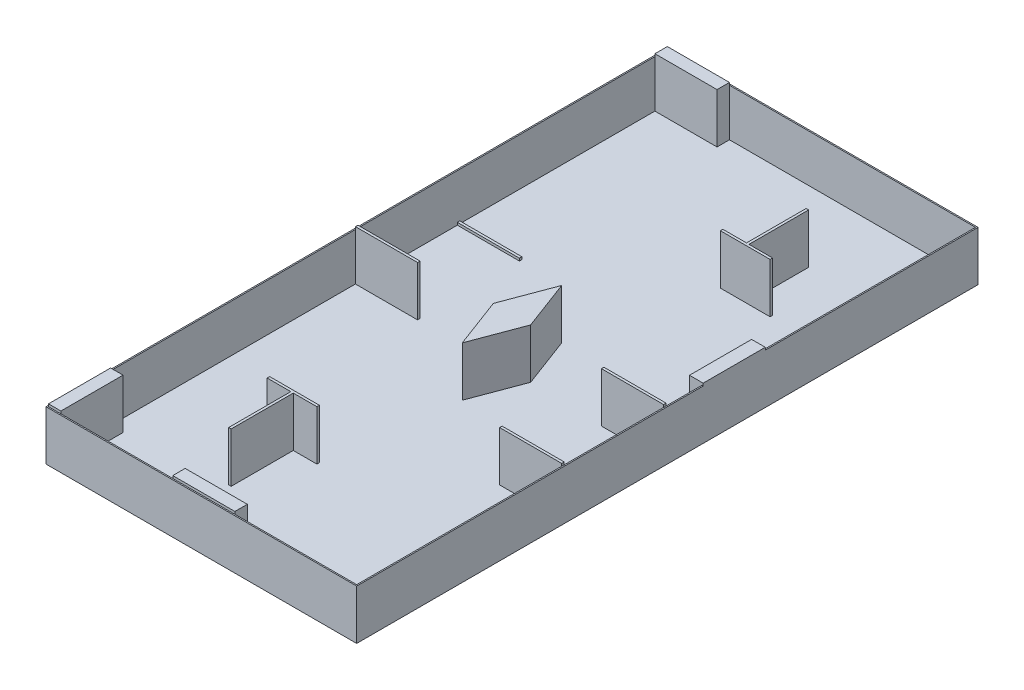
SolidWorks part; units mm, degrees
ref_plane "Front Plane" through (0, 0, 0) normal (0, 0, 1) x (1, 0, 0)
ref_plane "Top Plane" through (0, 0, 0) normal (0, 1, 0) x (1, 0, 0)
ref_plane "Right Plane" through (0, 0, 0) normal (1, 0, 0) x (0, 0, -1)
sketch "Sketch1" plane through (0, 0, 0) normal (0, 1, 0) x (1, 0, 0)
  line L1 (625, -1250) -> (-625, -1250)
  line L2 (625, -1250) -> (625, 1250)
  line L3 (625, 1250) -> (-625, 1250)
  line L4 (-625, -1250) -> (-625, 1250)
  line L5 (625, -1250) -> (-625, 1250) construction
  line L6 (625, 1250) -> (-625, -1250) construction
  point P0 (0, 0)
  dimension "D1" = 1250
  dimension "D2" = 2500
extrude "Boss-Extrude1" add sketch "Sketch1" along normal blind 200
sketch "Sketch2" plane through (0, 200, 0) normal (0, 1, 0) x (1, 0, 0)
  line L1 (620, -1245) -> (-620, -1245)
  line L2 (620, -1245) -> (620, 1245)
  line L3 (620, 1245) -> (-620, 1245)
  line L4 (-620, -1245) -> (-620, 1245)
  line L5 (620, -1245) -> (-620, 1245) construction
  line L6 (620, 1245) -> (-620, -1245) construction
  point P0 (0, 0)
  dimension "D1" = 1240
  dimension "D2" = 2490
extrude "Cut-Extrude1" cut sketch "Sketch2" against normal blind 190
sketch "Sketch6" plane through (0, 10, 0) normal (0, 1, 0) x (1, 0, 0)
  line L0 (-620, 1245) -> (-620, -1245) construction
  line L1 (-620, -1245) -> (620, -1245) construction
  line L2 (-620, 1245) -> (-620, -1245) construction
  point P0 (-170, -715)
  point P5 (-170, -705)
  dimension "D1" = 450
  dimension "D2" = 530
  dimension "D3" = 450
  dimension "D4" = 540
sketch "Sketch7" plane through (0, 10, 0) normal (0, 1, 0) x (1, 0, 0)
  line L0 (-170, -705) -> (-270, -705)
  line L1 (-270, -705) -> (-270, -715)
  line L2 (-270, -715) -> (-117.9067, -715)
  line L3 (-117.9067, -715) -> (-70, -715)
  line L4 (-70, -715) -> (-70, -705)
  line L5 (-70, -705) -> (-170, -705)
  dimension "D1" = 100
  dimension "D2" = 100
  dimension "D3" = 10
extrude "Boss-Extrude2" add sketch "Sketch7" along normal blind 200
sketch "Sketch8" plane through (0, 10, 0) normal (0, 1, 0) x (1, 0, 0)
  line L0 (-175, -715) -> (-165, -715)
  line L1 (-270, -715) -> (-70, -715) construction
  line L2 (-165, -715) -> (-165, -965)
  line L3 (-165, -965) -> (-175, -965)
  line L4 (-175, -965) -> (-175, -715)
  dimension "D1" = 5
  dimension "D2" = 5
  dimension "D3" = 10
  dimension "D4" = 250
extrude "Boss-Extrude3" add sketch "Sketch8" along normal blind 200
sketch "Sketch10" plane through (0, 10, 0) normal (0, 1, 0) x (1, 0, 0)
  line L0 (-620, 0) -> (-370, 0)
  line L1 (-620, 1245) -> (-620, -1245) construction
  line L2 (-625, 0) -> (625, 0) construction
  line L3 (-370, 0) -> (-370, -10)
  line L4 (-370, -10) -> (-620, -10)
  line L5 (-620, -10) -> (-620, 0)
  dimension "D1" = 250
  dimension "D2" = 10
extrude "Boss-Extrude4" add sketch "Sketch10" along normal blind 200
sketch "Sketch11" plane through (0, 10, 0) normal (0, 1, 0) x (1, 0, 0)
  line L0 (620, 0) -> (370, 0)
  line L1 (620, -1245) -> (620, 1245) construction
  line L2 (-625, 0) -> (625, 0) construction
  line L3 (370, 0) -> (370, -10)
  line L4 (370, -10) -> (620, -10)
  line L5 (620, -10) -> (620, 0)
  dimension "D1" = 250
  dimension "D2" = 10
extrude "Boss-Extrude8" add sketch "Sketch17" along normal blind 200
sketch "Sketch17" plane through (0, 10, 0) normal (0, 1, 0) x (1, 0, 0)
  line L0 (0, 200) -> (-75, 0)
  line L1 (-75, 0) -> (0, -200)
  line L2 (0, -200) -> (75, 0)
  line L3 (75, 0) -> (0, 200)
extrude "Boss-Extrude5" add sketch "Sketch11" along normal blind 200
sketch "Sketch12" plane through (0, 10, 0) normal (0, 1, 0) x (1, 0, 0)
  line L0 (620, -410) -> (370, -410)
  line L1 (620, -1245) -> (620, -10) construction
  line L2 (370, -410) -> (370, -420)
  line L3 (370, -420) -> (620, -420)
  line L4 (620, -420) -> (620, -410)
  dimension "D1" = 400
  dimension "D2" = 10
  dimension "D3" = 250
extrude "Boss-Extrude6" add sketch "Sketch12" along normal blind 200
sketch "Sketch15" plane through (0, 10, 0) normal (0, 1, 0) x (1, 0, 0)
  line L0 (0, -200) -> (0, 200)
  dimension "D1" = 200
  dimension "D2" = 200
sketch "Sketch16" plane through (0, 10, 0) normal (0, 1, 0) x (1, 0, 0)
  line L0 (-75, 0) -> (75, 0)
  line L1 (-625, 0) -> (625, 0) construction
  dimension "D1" = 75
  dimension "D2" = 75
sketch "Sketch18" plane through (0, 10, 0) normal (0, 1, 0) x (1, 0, 0)
  line L0 (-620, 400) -> (-370, 400)
  line L1 (-620, 1245) -> (-620, 0) construction
  line L2 (-370, 400) -> (-370, 410)
  line L3 (-370, 410) -> (-620, 410)
  line L4 (-620, 410) -> (-620, 400)
  dimension "D1" = 250
  dimension "D2" = 10
  dimension "D3" = 400
extrude "Boss-Extrude9" add sketch "Sketch18" along normal blind 10
sketch "Sketch19" plane through (0, 10, 0) normal (0, 1, 0) x (1, 0, 0)
  line L0 (625, 0) -> (-625, 0)
  line L1 (625, -1250) -> (625, 1250) construction
  line L2 (-625, 1250) -> (-625, -1250) construction
  line L7 (-625, 1250) -> (-625, -1250)
  line L8 (-625, -1250) -> (625, -1250)
  line L9 (625, -1250) -> (625, 1250)
  line L10 (625, 1250) -> (-625, 1250)
  line L11 (-625, 1250) -> (-625, 0)
  line L13 (625, 0) -> (625, 1250)
  line L14 (625, 1250) -> (-625, 1250)
  dimension "D1" = 0
sketch "Sketch20" plane through (0, 10, 0) normal (0, 1, 0) x (1, 0, 0)
  line L0 (620, 1245) -> (-620, 1245) construction
  line L1 (620, 0) -> (620, 1245) construction
  point P0 (170, 715)
  point P5 (170, 710)
  dimension "D1" = 530
  dimension "D2" = 450
  dimension "D3" = 450
  dimension "D4" = 535
sketch "Sketch21" plane through (0, 10, 0) normal (0, 1, 0) x (1, 0, 0)
  line L0 (170, 710) -> (328.5079, 710)
  line L1 (328.5079, 710) -> (328.5079, 720)
  line L2 (328.5079, 720) -> (233.5079, 720)
  line L3 (233.5079, 720) -> (233.5079, 960)
  line L4 (233.5079, 960) -> (223.5079, 960)
  line L5 (223.5079, 960) -> (223.5079, 720)
  line L6 (223.5079, 720) -> (128.5079, 720)
  line L7 (128.5079, 720) -> (128.5079, 710)
  line L8 (128.5079, 710) -> (170, 710)
  dimension "D1" = 95
  dimension "D2" = 95
  dimension "D3" = 10
  dimension "D4" = 10
  dimension "D5" = 10
  dimension "D6" = 240
extrude "Boss-Extrude10" add sketch "Sketch21" along normal blind 200
sketch "Sketch22" plane through (0, 10, 0) normal (0, 1, 0) x (1, 0, 0)
  line L0 (625, 0) -> (625, 1250)
  line L1 (625, 1250) -> (-625, 1250)
  line L2 (-625, 1250) -> (-620, 0)
sketch "Sketch23" plane through (0, 10, 0) normal (0, 1, 0) x (1, 0, 0)
  line L1 (-620, -1245) -> (-570, -1245)
  line L2 (-620, -1245) -> (-620, -995)
  line L3 (-620, -995) -> (-570, -995)
  line L4 (-570, -1245) -> (-570, -995)
  dimension "D1" = 50
  dimension "D2" = 250
extrude "Boss-Extrude11" add sketch "Sketch23" along normal blind 200
sketch "Sketch24" plane through (0, 10, 0) normal (0, 1, 0) x (1, 0, 0)
  line L0 (-570, -1245) -> (620, -1245) construction
  line L1 (-120, -1245) -> (130, -1245)
  line L2 (-120, -1245) -> (-120, -1195)
  line L3 (-120, -1195) -> (130, -1195)
  line L4 (130, -1245) -> (130, -1195)
  dimension "D1" = 250
  dimension "D2" = 50
  dimension "D3" = 500
extrude "Boss-Extrude12" add sketch "Sketch24" along normal blind 200
sketch "Sketch25" plane through (0, 10, 0) normal (0, 1, 0) x (1, 0, 0)
  line L1 (-620, 1245) -> (-370, 1245)
  line L2 (-620, 1245) -> (-620, 1195)
  line L3 (-620, 1195) -> (-370, 1195)
  line L4 (-370, 1245) -> (-370, 1195)
  dimension "D1" = 250
  dimension "D2" = 50
extrude "Boss-Extrude13" add sketch "Sketch25" along normal blind 200
sketch "Sketch26" plane through (0, 10, 0) normal (0, 1, 0) x (1, 0, 0)
  line L0 (625, 0) -> (625, 1250) construction
  line L1 (625, 394.1017) -> (570, 394.1017)
  line L2 (625, 394.1017) -> (625, 144.1017)
  line L3 (625, 144.1017) -> (570, 144.1017)
  line L4 (570, 394.1017) -> (570, 144.1017)
  dimension "D1" = 55
  dimension "D2" = 250
extrude "Boss-Extrude14" add sketch "Sketch26" along normal blind 200
sketch "Sketch28" plane through (0, 10, 0) normal (0, 1, 0) x (1, 0, 0)
  line L0 (-370, 1195) -> (570, 144.1017) construction
